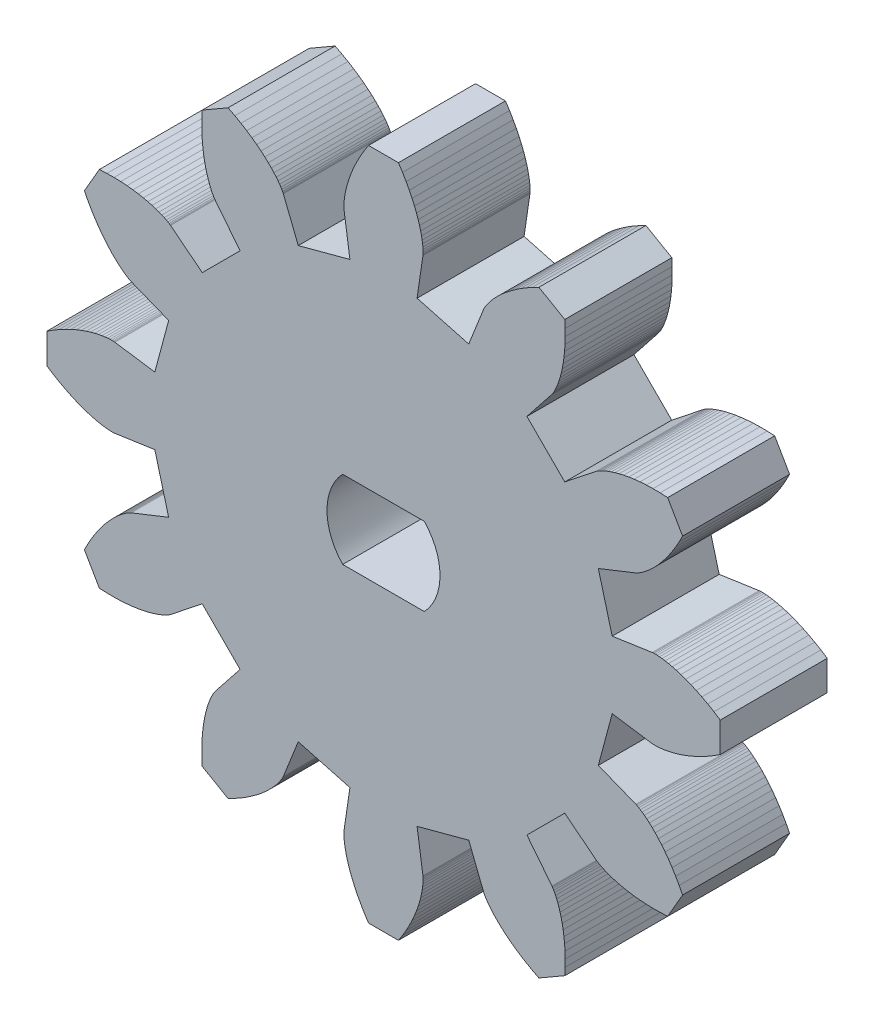
SolidWorks part; units mm, degrees
ref_plane "Front Plane" through (0, 0, 0) normal (0, 0, 1) x (1, 0, 0)
ref_plane "Top Plane" through (0, 0, 0) normal (0, 1, 0) x (1, 0, 0)
ref_plane "Right Plane" through (0, 0, 0) normal (1, 0, 0) x (0, 0, -1)
sketch "Model" plane through (0, 0, 0) normal (0, 0, 1) x (1, 0, 0)
  line L0 (10.6854, 1.5691) -> (12.5512, 1.8431)
  line L1 (12.5512, 1.8431) -> (12.5607, 1.8442)
  line L2 (12.5607, 1.8442) -> (12.5891, 1.8467)
  line L3 (12.5891, 1.8467) -> (12.6366, 1.8489)
  line L4 (12.6366, 1.8489) -> (12.7032, 1.8496)
  line L5 (12.7032, 1.8496) -> (12.7888, 1.8471)
  line L6 (12.7888, 1.8471) -> (12.8932, 1.84)
  line L7 (12.8932, 1.84) -> (13.0162, 1.8268)
  line L8 (13.0162, 1.8268) -> (13.1573, 1.8062)
  line L9 (13.1573, 1.8062) -> (13.3163, 1.7767)
  line L10 (13.3163, 1.7767) -> (13.4926, 1.7368)
  line L11 (13.4926, 1.7368) -> (13.6856, 1.6852)
  line L12 (13.6856, 1.6852) -> (13.8946, 1.6206)
  line L13 (13.8946, 1.6206) -> (14.1189, 1.5416)
  line L14 (14.1189, 1.5416) -> (14.3577, 1.447)
  line L15 (14.3577, 1.447) -> (14.6101, 1.3355)
  line L16 (14.6101, 1.3355) -> (14.875, 1.206)
  line L17 (14.875, 1.206) -> (15.1515, 1.0574)
  line L18 (15.1515, 1.0574) -> (15.4384, 0.8884)
  line L19 (15.4384, 0.8884) -> (15.7345, 0.6983)
  line L20 (15.7345, 0.6983) -> (15.7345, -0.6983)
  line L21 (15.7345, -0.6983) -> (15.4384, -0.8884)
  line L22 (15.4384, -0.8884) -> (15.1515, -1.0574)
  line L23 (15.1515, -1.0574) -> (14.875, -1.206)
  line L24 (14.875, -1.206) -> (14.6101, -1.3355)
  line L25 (14.6101, -1.3355) -> (14.3577, -1.447)
  line L26 (14.3577, -1.447) -> (14.1189, -1.5416)
  line L27 (14.1189, -1.5416) -> (13.8946, -1.6206)
  line L28 (13.8946, -1.6206) -> (13.6856, -1.6852)
  line L29 (13.6856, -1.6852) -> (13.4926, -1.7368)
  line L30 (13.4926, -1.7368) -> (13.3163, -1.7767)
  line L31 (13.3163, -1.7767) -> (13.1573, -1.8062)
  line L32 (13.1573, -1.8062) -> (13.0162, -1.8268)
  line L33 (13.0162, -1.8268) -> (12.8932, -1.84)
  line L34 (12.8932, -1.84) -> (12.7888, -1.8471)
  line L35 (12.7888, -1.8471) -> (12.7032, -1.8496)
  line L36 (12.7032, -1.8496) -> (12.6366, -1.8489)
  line L37 (12.6366, -1.8489) -> (12.5891, -1.8467)
  line L38 (12.5891, -1.8467) -> (12.5607, -1.8442)
  line L39 (12.5607, -1.8442) -> (12.5512, -1.8431)
  line L40 (12.5512, -1.8431) -> (10.6854, -1.5691)
  line L41 (10.6854, -1.5691) -> (10.0384, -3.9838)
  line L42 (10.0384, -3.9838) -> (11.7912, -4.6795)
  line L43 (11.7912, -4.6795) -> (11.8, -4.6832)
  line L44 (11.8, -4.6832) -> (11.8258, -4.6953)
  line L45 (11.8258, -4.6953) -> (11.8681, -4.7171)
  line L46 (11.8681, -4.7171) -> (11.9261, -4.7498)
  line L47 (11.9261, -4.7498) -> (11.999, -4.7948)
  line L48 (11.999, -4.7948) -> (12.0858, -4.8531)
  line L49 (12.0858, -4.8531) -> (12.1857, -4.926)
  line L50 (12.1857, -4.926) -> (12.2977, -5.0144)
  line L51 (12.2977, -5.0144) -> (12.4206, -5.1195)
  line L52 (12.4206, -5.1195) -> (12.5533, -5.2422)
  line L53 (12.5533, -5.2422) -> (12.6947, -5.3834)
  line L54 (12.6947, -5.3834) -> (12.8434, -5.5438)
  line L55 (12.8434, -5.5438) -> (12.9982, -5.7244)
  line L56 (12.9982, -5.7244) -> (13.1577, -5.9257)
  line L57 (13.1577, -5.9257) -> (13.3205, -6.1484)
  line L58 (13.3205, -6.1484) -> (13.4851, -6.393)
  line L59 (13.4851, -6.393) -> (13.6502, -6.66)
  line L60 (13.6502, -6.66) -> (13.8142, -6.9498)
  line L61 (13.8142, -6.9498) -> (13.9756, -7.2625)
  line L62 (13.9756, -7.2625) -> (13.2774, -8.472)
  line L63 (13.2774, -8.472) -> (12.9258, -8.4886)
  line L64 (12.9258, -8.4886) -> (12.5929, -8.4914)
  line L65 (12.5929, -8.4914) -> (12.2791, -8.482)
  line L66 (12.2791, -8.482) -> (11.9849, -8.4616)
  line L67 (11.9849, -8.4616) -> (11.7106, -8.432)
  line L68 (11.7106, -8.432) -> (11.4566, -8.3946)
  line L69 (11.4566, -8.3946) -> (11.2228, -8.3508)
  line L70 (11.2228, -8.3508) -> (11.0095, -8.3022)
  line L71 (11.0095, -8.3022) -> (10.8165, -8.2504)
  line L72 (10.8165, -8.2504) -> (10.6439, -8.1968)
  line L73 (10.6439, -8.1968) -> (10.4915, -8.1429)
  line L74 (10.4915, -8.1429) -> (10.3589, -8.0902)
  line L75 (10.3589, -8.0902) -> (10.2458, -8.0401)
  line L76 (10.2458, -8.0401) -> (10.1519, -7.994)
  line L77 (10.1519, -7.994) -> (10.0765, -7.9534)
  line L78 (10.0765, -7.9534) -> (10.0192, -7.9196)
  line L79 (10.0192, -7.9196) -> (9.9792, -7.8938)
  line L80 (9.9792, -7.8938) -> (9.9558, -7.8775)
  line L81 (9.9558, -7.8775) -> (9.9481, -7.8718)
  line L82 (9.9481, -7.8718) -> (8.4693, -6.7016)
  line L83 (8.4693, -6.7016) -> (6.7016, -8.4693)
  line L84 (6.7016, -8.4693) -> (7.8718, -9.9481)
  line L85 (7.8718, -9.9481) -> (7.8775, -9.9558)
  line L86 (7.8775, -9.9558) -> (7.8938, -9.9792)
  line L87 (7.8938, -9.9792) -> (7.9196, -10.0192)
  line L88 (7.9196, -10.0192) -> (7.9534, -10.0765)
  line L89 (7.9534, -10.0765) -> (7.994, -10.1519)
  line L90 (7.994, -10.1519) -> (8.0401, -10.2458)
  line L91 (8.0401, -10.2458) -> (8.0902, -10.3589)
  line L92 (8.0902, -10.3589) -> (8.1429, -10.4915)
  line L93 (8.1429, -10.4915) -> (8.1968, -10.6439)
  line L94 (8.1968, -10.6439) -> (8.2504, -10.8165)
  line L95 (8.2504, -10.8165) -> (8.3022, -11.0095)
  line L96 (8.3022, -11.0095) -> (8.3508, -11.2228)
  line L97 (8.3508, -11.2228) -> (8.3946, -11.4566)
  line L98 (8.3946, -11.4566) -> (8.432, -11.7106)
  line L99 (8.432, -11.7106) -> (8.4616, -11.9849)
  line L100 (8.4616, -11.9849) -> (8.482, -12.2791)
  line L101 (8.482, -12.2791) -> (8.4914, -12.5929)
  line L102 (8.4914, -12.5929) -> (8.4886, -12.9258)
  line L103 (8.4886, -12.9258) -> (8.472, -13.2774)
  line L104 (8.472, -13.2774) -> (7.2625, -13.9756)
  line L105 (7.2625, -13.9756) -> (6.9498, -13.8142)
  line L106 (6.9498, -13.8142) -> (6.66, -13.6502)
  line L107 (6.66, -13.6502) -> (6.393, -13.4851)
  line L108 (6.393, -13.4851) -> (6.1484, -13.3205)
  line L109 (6.1484, -13.3205) -> (5.9257, -13.1577)
  line L110 (5.9257, -13.1577) -> (5.7244, -12.9982)
  line L111 (5.7244, -12.9982) -> (5.5438, -12.8434)
  line L112 (5.5438, -12.8434) -> (5.3834, -12.6947)
  line L113 (5.3834, -12.6947) -> (5.2422, -12.5533)
  line L114 (5.2422, -12.5533) -> (5.1195, -12.4206)
  line L115 (5.1195, -12.4206) -> (5.0144, -12.2977)
  line L116 (5.0144, -12.2977) -> (4.926, -12.1857)
  line L117 (4.926, -12.1857) -> (4.8531, -12.0858)
  line L118 (4.8531, -12.0858) -> (4.7948, -11.999)
  line L119 (4.7948, -11.999) -> (4.7498, -11.9261)
  line L120 (4.7498, -11.9261) -> (4.7171, -11.8681)
  line L121 (4.7171, -11.8681) -> (4.6953, -11.8258)
  line L122 (4.6953, -11.8258) -> (4.6832, -11.8)
  line L123 (4.6832, -11.8) -> (4.6795, -11.7912)
  line L124 (4.6795, -11.7912) -> (3.9838, -10.0384)
  line L125 (3.9838, -10.0384) -> (1.5691, -10.6854)
  line L126 (1.5691, -10.6854) -> (1.8431, -12.5512)
  line L127 (1.8431, -12.5512) -> (1.8442, -12.5607)
  line L128 (1.8442, -12.5607) -> (1.8467, -12.5891)
  line L129 (1.8467, -12.5891) -> (1.8489, -12.6366)
  line L130 (1.8489, -12.6366) -> (1.8496, -12.7032)
  line L131 (1.8496, -12.7032) -> (1.8471, -12.7888)
  line L132 (1.8471, -12.7888) -> (1.84, -12.8932)
  line L133 (1.84, -12.8932) -> (1.8268, -13.0162)
  line L134 (1.8268, -13.0162) -> (1.8062, -13.1573)
  line L135 (1.8062, -13.1573) -> (1.7767, -13.3163)
  line L136 (1.7767, -13.3163) -> (1.7368, -13.4926)
  line L137 (1.7368, -13.4926) -> (1.6852, -13.6856)
  line L138 (1.6852, -13.6856) -> (1.6206, -13.8946)
  line L139 (1.6206, -13.8946) -> (1.5416, -14.1189)
  line L140 (1.5416, -14.1189) -> (1.447, -14.3577)
  line L141 (1.447, -14.3577) -> (1.3355, -14.6101)
  line L142 (1.3355, -14.6101) -> (1.206, -14.875)
  line L143 (1.206, -14.875) -> (1.0574, -15.1515)
  line L144 (1.0574, -15.1515) -> (0.8884, -15.4384)
  line L145 (0.8884, -15.4384) -> (0.6983, -15.7345)
  line L146 (0.6983, -15.7345) -> (-0.6983, -15.7345)
  line L147 (-0.6983, -15.7345) -> (-0.8884, -15.4384)
  line L148 (-0.8884, -15.4384) -> (-1.0574, -15.1515)
  line L149 (-1.0574, -15.1515) -> (-1.206, -14.875)
  line L150 (-1.206, -14.875) -> (-1.3355, -14.6101)
  line L151 (-1.3355, -14.6101) -> (-1.447, -14.3577)
  line L152 (-1.447, -14.3577) -> (-1.5416, -14.1189)
  line L153 (-1.5416, -14.1189) -> (-1.6206, -13.8946)
  line L154 (-1.6206, -13.8946) -> (-1.6852, -13.6856)
  line L155 (-1.6852, -13.6856) -> (-1.7368, -13.4926)
  line L156 (-1.7368, -13.4926) -> (-1.7767, -13.3163)
  line L157 (-1.7767, -13.3163) -> (-1.8062, -13.1573)
  line L158 (-1.8062, -13.1573) -> (-1.8268, -13.0162)
  line L159 (-1.8268, -13.0162) -> (-1.84, -12.8932)
  line L160 (-1.84, -12.8932) -> (-1.8471, -12.7888)
  line L161 (-1.8471, -12.7888) -> (-1.8496, -12.7032)
  line L162 (-1.8496, -12.7032) -> (-1.8489, -12.6366)
  line L163 (-1.8489, -12.6366) -> (-1.8467, -12.5891)
  line L164 (-1.8467, -12.5891) -> (-1.8442, -12.5607)
  line L165 (-1.8442, -12.5607) -> (-1.8431, -12.5512)
  line L166 (-1.8431, -12.5512) -> (-1.5691, -10.6854)
  line L167 (-1.5691, -10.6854) -> (-3.9838, -10.0384)
  line L168 (-3.9838, -10.0384) -> (-4.6795, -11.7912)
  line L169 (-4.6795, -11.7912) -> (-4.6832, -11.8)
  line L170 (-4.6832, -11.8) -> (-4.6953, -11.8258)
  line L171 (-4.6953, -11.8258) -> (-4.7171, -11.8681)
  line L172 (-4.7171, -11.8681) -> (-4.7498, -11.9261)
  line L173 (-4.7498, -11.9261) -> (-4.7948, -11.999)
  line L174 (-4.7948, -11.999) -> (-4.8531, -12.0858)
  line L175 (-4.8531, -12.0858) -> (-4.926, -12.1857)
  line L176 (-4.926, -12.1857) -> (-5.0144, -12.2977)
  line L177 (-5.0144, -12.2977) -> (-5.1195, -12.4206)
  line L178 (-5.1195, -12.4206) -> (-5.2422, -12.5533)
  line L179 (-5.2422, -12.5533) -> (-5.3834, -12.6947)
  line L180 (-5.3834, -12.6947) -> (-5.5438, -12.8434)
  line L181 (-5.5438, -12.8434) -> (-5.7244, -12.9982)
  line L182 (-5.7244, -12.9982) -> (-5.9257, -13.1577)
  line L183 (-5.9257, -13.1577) -> (-6.1484, -13.3205)
  line L184 (-6.1484, -13.3205) -> (-6.393, -13.4851)
  line L185 (-6.393, -13.4851) -> (-6.66, -13.6502)
  line L186 (-6.66, -13.6502) -> (-6.9498, -13.8142)
  line L187 (-6.9498, -13.8142) -> (-7.2625, -13.9756)
  line L188 (-7.2625, -13.9756) -> (-8.472, -13.2774)
  line L189 (-8.472, -13.2774) -> (-8.4886, -12.9258)
  line L190 (-8.4886, -12.9258) -> (-8.4914, -12.5929)
  line L191 (-8.4914, -12.5929) -> (-8.482, -12.2791)
  line L192 (-8.482, -12.2791) -> (-8.4616, -11.9849)
  line L193 (-8.4616, -11.9849) -> (-8.432, -11.7106)
  line L194 (-8.432, -11.7106) -> (-8.3946, -11.4566)
  line L195 (-8.3946, -11.4566) -> (-8.3508, -11.2228)
  line L196 (-8.3508, -11.2228) -> (-8.3022, -11.0095)
  line L197 (-8.3022, -11.0095) -> (-8.2504, -10.8165)
  line L198 (-8.2504, -10.8165) -> (-8.1968, -10.6439)
  line L199 (-8.1968, -10.6439) -> (-8.1429, -10.4915)
  line L200 (-8.1429, -10.4915) -> (-8.0902, -10.3589)
  line L201 (-8.0902, -10.3589) -> (-8.0401, -10.2458)
  line L202 (-8.0401, -10.2458) -> (-7.994, -10.1519)
  line L203 (-7.994, -10.1519) -> (-7.9534, -10.0765)
  line L204 (-7.9534, -10.0765) -> (-7.9196, -10.0192)
  line L205 (-7.9196, -10.0192) -> (-7.8938, -9.9792)
  line L206 (-7.8938, -9.9792) -> (-7.8775, -9.9558)
  line L207 (-7.8775, -9.9558) -> (-7.8718, -9.9481)
  line L208 (-7.8718, -9.9481) -> (-6.7016, -8.4693)
  line L209 (-6.7016, -8.4693) -> (-8.4693, -6.7016)
  line L210 (-8.4693, -6.7016) -> (-9.9481, -7.8718)
  line L211 (-9.9481, -7.8718) -> (-9.9558, -7.8775)
  line L212 (-9.9558, -7.8775) -> (-9.9792, -7.8938)
  line L213 (-9.9792, -7.8938) -> (-10.0192, -7.9196)
  line L214 (-10.0192, -7.9196) -> (-10.0765, -7.9534)
  line L215 (-10.0765, -7.9534) -> (-10.1519, -7.994)
  line L216 (-10.1519, -7.994) -> (-10.2458, -8.0401)
  line L217 (-10.2458, -8.0401) -> (-10.3589, -8.0902)
  line L218 (-10.3589, -8.0902) -> (-10.4915, -8.1429)
  line L219 (-10.4915, -8.1429) -> (-10.6439, -8.1968)
  line L220 (-10.6439, -8.1968) -> (-10.8165, -8.2504)
  line L221 (-10.8165, -8.2504) -> (-11.0095, -8.3022)
  line L222 (-11.0095, -8.3022) -> (-11.2228, -8.3508)
  line L223 (-11.2228, -8.3508) -> (-11.4566, -8.3946)
  line L224 (-11.4566, -8.3946) -> (-11.7106, -8.432)
  line L225 (-11.7106, -8.432) -> (-11.9849, -8.4616)
  line L226 (-11.9849, -8.4616) -> (-12.2791, -8.482)
  line L227 (-12.2791, -8.482) -> (-12.5929, -8.4914)
  line L228 (-12.5929, -8.4914) -> (-12.9258, -8.4886)
  line L229 (-12.9258, -8.4886) -> (-13.2774, -8.472)
  line L230 (-13.2774, -8.472) -> (-13.9756, -7.2625)
  line L231 (-13.9756, -7.2625) -> (-13.8142, -6.9498)
  line L232 (-13.8142, -6.9498) -> (-13.6502, -6.66)
  line L233 (-13.6502, -6.66) -> (-13.4851, -6.393)
  line L234 (-13.4851, -6.393) -> (-13.3205, -6.1484)
  line L235 (-13.3205, -6.1484) -> (-13.1577, -5.9257)
  line L236 (-13.1577, -5.9257) -> (-12.9982, -5.7244)
  line L237 (-12.9982, -5.7244) -> (-12.8434, -5.5438)
  line L238 (-12.8434, -5.5438) -> (-12.6947, -5.3834)
  line L239 (-12.6947, -5.3834) -> (-12.5533, -5.2422)
  line L240 (-12.5533, -5.2422) -> (-12.4206, -5.1195)
  line L241 (-12.4206, -5.1195) -> (-12.2977, -5.0144)
  line L242 (-12.2977, -5.0144) -> (-12.1857, -4.926)
  line L243 (-12.1857, -4.926) -> (-12.0858, -4.8531)
  line L244 (-12.0858, -4.8531) -> (-11.999, -4.7948)
  line L245 (-11.999, -4.7948) -> (-11.9261, -4.7498)
  line L246 (-11.9261, -4.7498) -> (-11.8681, -4.7171)
  line L247 (-11.8681, -4.7171) -> (-11.8258, -4.6953)
  line L248 (-11.8258, -4.6953) -> (-11.8, -4.6832)
  line L249 (-11.8, -4.6832) -> (-11.7912, -4.6795)
  line L250 (-11.7912, -4.6795) -> (-10.0384, -3.9838)
  line L251 (-10.0384, -3.9838) -> (-10.6854, -1.5691)
  line L252 (-10.6854, -1.5691) -> (-12.5512, -1.8431)
  line L253 (-12.5512, -1.8431) -> (-12.5607, -1.8442)
  line L254 (-12.5607, -1.8442) -> (-12.5891, -1.8467)
  line L255 (-12.5891, -1.8467) -> (-12.6366, -1.8489)
  line L256 (-12.6366, -1.8489) -> (-12.7032, -1.8496)
  line L257 (-12.7032, -1.8496) -> (-12.7888, -1.8471)
  line L258 (-12.7888, -1.8471) -> (-12.8932, -1.84)
  line L259 (-12.8932, -1.84) -> (-13.0162, -1.8268)
  line L260 (-13.0162, -1.8268) -> (-13.1573, -1.8062)
  line L261 (-13.1573, -1.8062) -> (-13.3163, -1.7767)
  line L262 (-13.3163, -1.7767) -> (-13.4926, -1.7368)
  line L263 (-13.4926, -1.7368) -> (-13.6856, -1.6852)
  line L264 (-13.6856, -1.6852) -> (-13.8946, -1.6206)
  line L265 (-13.8946, -1.6206) -> (-14.1189, -1.5416)
  line L266 (-14.1189, -1.5416) -> (-14.3577, -1.447)
  line L267 (-14.3577, -1.447) -> (-14.6101, -1.3355)
  line L268 (-14.6101, -1.3355) -> (-14.875, -1.206)
  line L269 (-14.875, -1.206) -> (-15.1515, -1.0574)
  line L270 (-15.1515, -1.0574) -> (-15.4384, -0.8884)
  line L271 (-15.4384, -0.8884) -> (-15.7345, -0.6983)
  line L272 (-15.7345, -0.6983) -> (-15.7345, 0.6983)
  line L273 (-15.7345, 0.6983) -> (-15.4384, 0.8884)
  line L274 (-15.4384, 0.8884) -> (-15.1515, 1.0574)
  line L275 (-15.1515, 1.0574) -> (-14.875, 1.206)
  line L276 (-14.875, 1.206) -> (-14.6101, 1.3355)
  line L277 (-14.6101, 1.3355) -> (-14.3577, 1.447)
  line L278 (-14.3577, 1.447) -> (-14.1189, 1.5416)
  line L279 (-14.1189, 1.5416) -> (-13.8946, 1.6206)
  line L280 (-13.8946, 1.6206) -> (-13.6856, 1.6852)
  line L281 (-13.6856, 1.6852) -> (-13.4926, 1.7368)
  line L282 (-13.4926, 1.7368) -> (-13.3163, 1.7767)
  line L283 (-13.3163, 1.7767) -> (-13.1573, 1.8062)
  line L284 (-13.1573, 1.8062) -> (-13.0162, 1.8268)
  line L285 (-13.0162, 1.8268) -> (-12.8932, 1.84)
  line L286 (-12.8932, 1.84) -> (-12.7888, 1.8471)
  line L287 (-12.7888, 1.8471) -> (-12.7032, 1.8496)
  line L288 (-12.7032, 1.8496) -> (-12.6366, 1.8489)
  line L289 (-12.6366, 1.8489) -> (-12.5891, 1.8467)
  line L290 (-12.5891, 1.8467) -> (-12.5607, 1.8442)
  line L291 (-12.5607, 1.8442) -> (-12.5512, 1.8431)
  line L292 (-12.5512, 1.8431) -> (-10.6854, 1.5691)
  line L293 (-10.6854, 1.5691) -> (-10.0384, 3.9838)
  line L294 (-10.0384, 3.9838) -> (-11.7912, 4.6795)
  line L295 (-11.7912, 4.6795) -> (-11.8, 4.6832)
  line L296 (-11.8, 4.6832) -> (-11.8258, 4.6953)
  line L297 (-11.8258, 4.6953) -> (-11.8681, 4.7171)
  line L298 (-11.8681, 4.7171) -> (-11.9261, 4.7498)
  line L299 (-11.9261, 4.7498) -> (-11.999, 4.7948)
  line L300 (-11.999, 4.7948) -> (-12.0858, 4.8531)
  line L301 (-12.0858, 4.8531) -> (-12.1857, 4.926)
  line L302 (-12.1857, 4.926) -> (-12.2977, 5.0144)
  line L303 (-12.2977, 5.0144) -> (-12.4206, 5.1195)
  line L304 (-12.4206, 5.1195) -> (-12.5533, 5.2422)
  line L305 (-12.5533, 5.2422) -> (-12.6947, 5.3834)
  line L306 (-12.6947, 5.3834) -> (-12.8434, 5.5438)
  line L307 (-12.8434, 5.5438) -> (-12.9982, 5.7244)
  line L308 (-12.9982, 5.7244) -> (-13.1577, 5.9257)
  line L309 (-13.1577, 5.9257) -> (-13.3205, 6.1484)
  line L310 (-13.3205, 6.1484) -> (-13.4851, 6.393)
  line L311 (-13.4851, 6.393) -> (-13.6502, 6.66)
  line L312 (-13.6502, 6.66) -> (-13.8142, 6.9498)
  line L313 (-13.8142, 6.9498) -> (-13.9756, 7.2625)
  line L314 (-13.9756, 7.2625) -> (-13.2774, 8.472)
  line L315 (-13.2774, 8.472) -> (-12.9258, 8.4886)
  line L316 (-12.9258, 8.4886) -> (-12.5929, 8.4914)
  line L317 (-12.5929, 8.4914) -> (-12.2791, 8.482)
  line L318 (-12.2791, 8.482) -> (-11.9849, 8.4616)
  line L319 (-11.9849, 8.4616) -> (-11.7106, 8.432)
  line L320 (-11.7106, 8.432) -> (-11.4566, 8.3946)
  line L321 (-11.4566, 8.3946) -> (-11.2228, 8.3508)
  line L322 (-11.2228, 8.3508) -> (-11.0095, 8.3022)
  line L323 (-11.0095, 8.3022) -> (-10.8165, 8.2504)
  line L324 (-10.8165, 8.2504) -> (-10.6439, 8.1968)
  line L325 (-10.6439, 8.1968) -> (-10.4915, 8.1429)
  line L326 (-10.4915, 8.1429) -> (-10.3589, 8.0902)
  line L327 (-10.3589, 8.0902) -> (-10.2458, 8.0401)
  line L328 (-10.2458, 8.0401) -> (-10.1519, 7.994)
  line L329 (-10.1519, 7.994) -> (-10.0765, 7.9534)
  line L330 (-10.0765, 7.9534) -> (-10.0192, 7.9196)
  line L331 (-10.0192, 7.9196) -> (-9.9792, 7.8938)
  line L332 (-9.9792, 7.8938) -> (-9.9558, 7.8775)
  line L333 (-9.9558, 7.8775) -> (-9.9481, 7.8718)
  line L334 (-9.9481, 7.8718) -> (-8.4693, 6.7016)
  line L335 (-8.4693, 6.7016) -> (-6.7016, 8.4693)
  line L336 (-6.7016, 8.4693) -> (-7.8718, 9.9481)
  line L337 (-7.8718, 9.9481) -> (-7.8775, 9.9558)
  line L338 (-7.8775, 9.9558) -> (-7.8938, 9.9792)
  line L339 (-7.8938, 9.9792) -> (-7.9196, 10.0192)
  line L340 (-7.9196, 10.0192) -> (-7.9534, 10.0765)
  line L341 (-7.9534, 10.0765) -> (-7.994, 10.1519)
  line L342 (-7.994, 10.1519) -> (-8.0401, 10.2458)
  line L343 (-8.0401, 10.2458) -> (-8.0902, 10.3589)
  line L344 (-8.0902, 10.3589) -> (-8.1429, 10.4915)
  line L345 (-8.1429, 10.4915) -> (-8.1968, 10.6439)
  line L346 (-8.1968, 10.6439) -> (-8.2504, 10.8165)
  line L347 (-8.2504, 10.8165) -> (-8.3022, 11.0095)
  line L348 (-8.3022, 11.0095) -> (-8.3508, 11.2228)
  line L349 (-8.3508, 11.2228) -> (-8.3946, 11.4566)
  line L350 (-8.3946, 11.4566) -> (-8.432, 11.7106)
  line L351 (-8.432, 11.7106) -> (-8.4616, 11.9849)
  line L352 (-8.4616, 11.9849) -> (-8.482, 12.2791)
  line L353 (-8.482, 12.2791) -> (-8.4914, 12.5929)
  line L354 (-8.4914, 12.5929) -> (-8.4886, 12.9258)
  line L355 (-8.4886, 12.9258) -> (-8.472, 13.2774)
  line L356 (-8.472, 13.2774) -> (-7.2625, 13.9756)
  line L357 (-7.2625, 13.9756) -> (-6.9498, 13.8142)
  line L358 (-6.9498, 13.8142) -> (-6.66, 13.6502)
  line L359 (-6.66, 13.6502) -> (-6.393, 13.4851)
  line L360 (-6.393, 13.4851) -> (-6.1484, 13.3205)
  line L361 (-6.1484, 13.3205) -> (-5.9257, 13.1577)
  line L362 (-5.9257, 13.1577) -> (-5.7244, 12.9982)
  line L363 (-5.7244, 12.9982) -> (-5.5438, 12.8434)
  line L364 (-5.5438, 12.8434) -> (-5.3834, 12.6947)
  line L365 (-5.3834, 12.6947) -> (-5.2422, 12.5533)
  line L366 (-5.2422, 12.5533) -> (-5.1195, 12.4206)
  line L367 (-5.1195, 12.4206) -> (-5.0144, 12.2977)
  line L368 (-5.0144, 12.2977) -> (-4.926, 12.1857)
  line L369 (-4.926, 12.1857) -> (-4.8531, 12.0858)
  line L370 (-4.8531, 12.0858) -> (-4.7948, 11.999)
  line L371 (-4.7948, 11.999) -> (-4.7498, 11.9261)
  line L372 (-4.7498, 11.9261) -> (-4.7171, 11.8681)
  line L373 (-4.7171, 11.8681) -> (-4.6953, 11.8258)
  line L374 (-4.6953, 11.8258) -> (-4.6832, 11.8)
  line L375 (-4.6832, 11.8) -> (-4.6795, 11.7912)
  line L376 (-4.6795, 11.7912) -> (-3.9838, 10.0384)
  line L377 (-3.9838, 10.0384) -> (-1.5691, 10.6854)
  line L378 (-1.5691, 10.6854) -> (-1.8431, 12.5512)
  line L379 (-1.8431, 12.5512) -> (-1.8442, 12.5607)
  line L380 (-1.8442, 12.5607) -> (-1.8467, 12.5891)
  line L381 (-1.8467, 12.5891) -> (-1.8489, 12.6366)
  line L382 (-1.8489, 12.6366) -> (-1.8496, 12.7032)
  line L383 (-1.8496, 12.7032) -> (-1.8471, 12.7888)
  line L384 (-1.8471, 12.7888) -> (-1.84, 12.8932)
  line L385 (-1.84, 12.8932) -> (-1.8268, 13.0162)
  line L386 (-1.8268, 13.0162) -> (-1.8062, 13.1573)
  line L387 (-1.8062, 13.1573) -> (-1.7767, 13.3163)
  line L388 (-1.7767, 13.3163) -> (-1.7368, 13.4926)
  line L389 (-1.7368, 13.4926) -> (-1.6852, 13.6856)
  line L390 (-1.6852, 13.6856) -> (-1.6206, 13.8946)
  line L391 (-1.6206, 13.8946) -> (-1.5416, 14.1189)
  line L392 (-1.5416, 14.1189) -> (-1.447, 14.3577)
  line L393 (-1.447, 14.3577) -> (-1.3355, 14.6101)
  line L394 (-1.3355, 14.6101) -> (-1.206, 14.875)
  line L395 (-1.206, 14.875) -> (-1.0574, 15.1515)
  line L396 (-1.0574, 15.1515) -> (-0.8884, 15.4384)
  line L397 (-0.8884, 15.4384) -> (-0.6983, 15.7345)
  line L398 (-0.6983, 15.7345) -> (0.6983, 15.7345)
  line L399 (0.6983, 15.7345) -> (0.8884, 15.4384)
  line L400 (0.8884, 15.4384) -> (1.0574, 15.1515)
  line L401 (1.0574, 15.1515) -> (1.206, 14.875)
  line L402 (1.206, 14.875) -> (1.3355, 14.6101)
  line L403 (1.3355, 14.6101) -> (1.447, 14.3577)
  line L404 (1.447, 14.3577) -> (1.5416, 14.1189)
  line L405 (1.5416, 14.1189) -> (1.6206, 13.8946)
  line L406 (1.6206, 13.8946) -> (1.6852, 13.6856)
  line L407 (1.6852, 13.6856) -> (1.7368, 13.4926)
  line L408 (1.7368, 13.4926) -> (1.7767, 13.3163)
  line L409 (1.7767, 13.3163) -> (1.8062, 13.1573)
  line L410 (1.8062, 13.1573) -> (1.8268, 13.0162)
  line L411 (1.8268, 13.0162) -> (1.84, 12.8932)
  line L412 (1.84, 12.8932) -> (1.8471, 12.7888)
  line L413 (1.8471, 12.7888) -> (1.8496, 12.7032)
  line L414 (1.8496, 12.7032) -> (1.8489, 12.6366)
  line L415 (1.8489, 12.6366) -> (1.8467, 12.5891)
  line L416 (1.8467, 12.5891) -> (1.8442, 12.5607)
  line L417 (1.8442, 12.5607) -> (1.8431, 12.5512)
  line L418 (1.8431, 12.5512) -> (1.5691, 10.6854)
  line L419 (1.5691, 10.6854) -> (3.9838, 10.0384)
  line L420 (3.9838, 10.0384) -> (4.6795, 11.7912)
  line L421 (4.6795, 11.7912) -> (4.6832, 11.8)
  line L422 (4.6832, 11.8) -> (4.6953, 11.8258)
  line L423 (4.6953, 11.8258) -> (4.7171, 11.8681)
  line L424 (4.7171, 11.8681) -> (4.7498, 11.9261)
  line L425 (4.7498, 11.9261) -> (4.7948, 11.999)
  line L426 (4.7948, 11.999) -> (4.8531, 12.0858)
  line L427 (4.8531, 12.0858) -> (4.926, 12.1857)
  line L428 (4.926, 12.1857) -> (5.0144, 12.2977)
  line L429 (5.0144, 12.2977) -> (5.1195, 12.4206)
  line L430 (5.1195, 12.4206) -> (5.2422, 12.5533)
  line L431 (5.2422, 12.5533) -> (5.3834, 12.6947)
  line L432 (5.3834, 12.6947) -> (5.5438, 12.8434)
  line L433 (5.5438, 12.8434) -> (5.7244, 12.9982)
  line L434 (5.7244, 12.9982) -> (5.9257, 13.1577)
  line L435 (5.9257, 13.1577) -> (6.1484, 13.3205)
  line L436 (6.1484, 13.3205) -> (6.393, 13.4851)
  line L437 (6.393, 13.4851) -> (6.66, 13.6502)
  line L438 (6.66, 13.6502) -> (6.9498, 13.8142)
  line L439 (6.9498, 13.8142) -> (7.2625, 13.9756)
  line L440 (7.2625, 13.9756) -> (8.472, 13.2774)
  line L441 (8.472, 13.2774) -> (8.4886, 12.9258)
  line L442 (8.4886, 12.9258) -> (8.4914, 12.5929)
  line L443 (8.4914, 12.5929) -> (8.482, 12.2791)
  line L444 (8.482, 12.2791) -> (8.4616, 11.9849)
  line L445 (8.4616, 11.9849) -> (8.432, 11.7106)
  line L446 (8.432, 11.7106) -> (8.3946, 11.4566)
  line L447 (8.3946, 11.4566) -> (8.3508, 11.2228)
  line L448 (8.3508, 11.2228) -> (8.3022, 11.0095)
  line L449 (8.3022, 11.0095) -> (8.2504, 10.8165)
  line L450 (8.2504, 10.8165) -> (8.1968, 10.6439)
  line L451 (8.1968, 10.6439) -> (8.1429, 10.4915)
  line L452 (8.1429, 10.4915) -> (8.0902, 10.3589)
  line L453 (8.0902, 10.3589) -> (8.0401, 10.2458)
  line L454 (8.0401, 10.2458) -> (7.994, 10.1519)
  line L455 (7.994, 10.1519) -> (7.9534, 10.0765)
  line L456 (7.9534, 10.0765) -> (7.9196, 10.0192)
  line L457 (7.9196, 10.0192) -> (7.8938, 9.9792)
  line L458 (7.8938, 9.9792) -> (7.8775, 9.9558)
  line L459 (7.8775, 9.9558) -> (7.8718, 9.9481)
  line L460 (7.8718, 9.9481) -> (6.7016, 8.4693)
  line L461 (6.7016, 8.4693) -> (8.4693, 6.7016)
  line L462 (8.4693, 6.7016) -> (9.9481, 7.8718)
  line L463 (9.9481, 7.8718) -> (9.9558, 7.8775)
  line L464 (9.9558, 7.8775) -> (9.9792, 7.8938)
  line L465 (9.9792, 7.8938) -> (10.0192, 7.9196)
  line L466 (10.0192, 7.9196) -> (10.0765, 7.9534)
  line L467 (10.0765, 7.9534) -> (10.1519, 7.994)
  line L468 (10.1519, 7.994) -> (10.2458, 8.0401)
  line L469 (10.2458, 8.0401) -> (10.3589, 8.0902)
  line L470 (10.3589, 8.0902) -> (10.4915, 8.1429)
  line L471 (10.4915, 8.1429) -> (10.6439, 8.1968)
  line L472 (10.6439, 8.1968) -> (10.8165, 8.2504)
  line L473 (10.8165, 8.2504) -> (11.0095, 8.3022)
  line L474 (11.0095, 8.3022) -> (11.2228, 8.3508)
  line L475 (11.2228, 8.3508) -> (11.4566, 8.3946)
  line L476 (11.4566, 8.3946) -> (11.7106, 8.432)
  line L477 (11.7106, 8.432) -> (11.9849, 8.4616)
  line L478 (11.9849, 8.4616) -> (12.2791, 8.482)
  line L479 (12.2791, 8.482) -> (12.5929, 8.4914)
  line L480 (12.5929, 8.4914) -> (12.9258, 8.4886)
  line L481 (12.9258, 8.4886) -> (13.2774, 8.472)
  line L482 (13.2774, 8.472) -> (13.9756, 7.2625)
  line L483 (13.9756, 7.2625) -> (13.8142, 6.9498)
  line L484 (13.8142, 6.9498) -> (13.6502, 6.66)
  line L485 (13.6502, 6.66) -> (13.4851, 6.393)
  line L486 (13.4851, 6.393) -> (13.3205, 6.1484)
  line L487 (13.3205, 6.1484) -> (13.1577, 5.9257)
  line L488 (13.1577, 5.9257) -> (12.9982, 5.7244)
  line L489 (12.9982, 5.7244) -> (12.8434, 5.5438)
  line L490 (12.8434, 5.5438) -> (12.6947, 5.3834)
  line L491 (12.6947, 5.3834) -> (12.5533, 5.2422)
  line L492 (12.5533, 5.2422) -> (12.4206, 5.1195)
  line L493 (12.4206, 5.1195) -> (12.2977, 5.0144)
  line L494 (12.2977, 5.0144) -> (12.1857, 4.926)
  line L495 (12.1857, 4.926) -> (12.0858, 4.8531)
  line L496 (12.0858, 4.8531) -> (11.999, 4.7948)
  line L497 (11.999, 4.7948) -> (11.9261, 4.7498)
  line L498 (11.9261, 4.7498) -> (11.8681, 4.7171)
  line L499 (11.8681, 4.7171) -> (11.8258, 4.6953)
  line L500 (11.8258, 4.6953) -> (11.8, 4.6832)
  line L501 (11.8, 4.6832) -> (11.7912, 4.6795)
  line L502 (11.7912, 4.6795) -> (10.0384, 3.9838)
  line L503 (10.0384, 3.9838) -> (10.6854, 1.5691)
extrude "Boss-Extrude1" add sketch "Model" along normal blind 5
sketch "Sketch3" plane through (0, 0, 5) normal (0, 0, 1) x (1, 0, 0)
  line L0 (1.9076, 1.825) -> (-1.9076, 1.825)
  line L1 (-1.9076, -1.825) -> (1.9076, -1.825)
  arc A0 (-1.9076, 1.825) -> (-1.9076, -1.825) centre (0, 0) ccw
  arc A1 (1.9076, -1.825) -> (1.9076, 1.825) centre (0, 0) ccw
  point P5 (0, 0)
  dimension "D1" = 5.28
  dimension "D2" = 3.65
  dimension "D3" = 1.825
  dimension "D4" = 1.825
extrude "Cut-Extrude1" cut sketch "Sketch3" against normal blind 5
